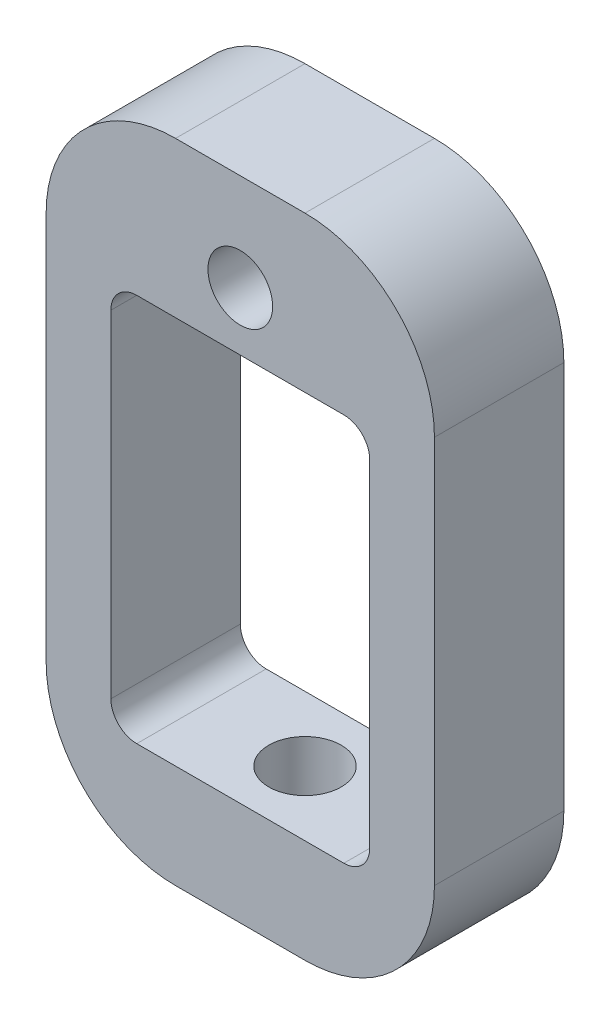
SolidWorks part; units mm, degrees
ref_plane "Front Plane" through (0, 0, 0) normal (0, 0, 1) x (1, 0, 0)
ref_plane "Top Plane" through (0, 0, 0) normal (0, 1, 0) x (1, 0, 0)
ref_plane "Right Plane" through (0, 0, 0) normal (1, 0, 0) x (0, 0, -1)
sketch "Sketch1" plane through (0, 0, 0) normal (0, 0, 1) x (1, 0, 0)
  line L0 (7.5, -25) -> (7.5, 0) construction
  line L1 (0, 0) -> (15, 0)
  line L2 (0, 0) -> (0, -25)
  line L3 (0, -25) -> (15, -25)
  line L4 (15, 0) -> (15, -25)
  line L5 (2.5, -6) -> (12.5, -6)
  line L6 (2.5, -6) -> (2.5, -21)
  line L7 (2.5, -21) -> (12.5, -21)
  line L8 (12.5, -6) -> (12.5, -21)
  line L9 (0, -12.5) -> (15, -12.5) construction
  line L10 (7.5, 0) -> (7.5, -1.75) construction
  circle A0 centre (7.5, -3.75) radius 1.25
  point P15 (7.5, -6)
  dimension "D5" = 2.5
  dimension "D1" = 15
  dimension "D2" = 25
  dimension "D3" = 10
  dimension "D4" = 15
  dimension "D6" = 3.75
  dimension "D7" = 6
extrude "Boss-Extrude1" add sketch "Sketch1" along normal blind 5 contours L8 L7 L6 L5
sketch "Sketch2" plane through (0, -25, 0) normal (0, -1, 0) x (1, 0, 0)
  line L0 (7.5, 0) -> (7.5, 5) construction
  line L1 (0, 0) -> (15, 0) construction
  line L2 (0, 5) -> (15, 5) construction
  line L3 (0, 2.5) -> (7.5, 2.5) construction
  line L4 (0, 5) -> (0, 0) construction
  circle A0 centre (7.5, 2.5) radius 1.4
  dimension "D1" = 2.8
extrude "Cut-Extrude1" cut sketch "Sketch2" against normal up to surface (4 mm away) up to face at (7.5, -21, 2.5)
fillet "Fillet1" radius 5 4 edges at (15, -25, 2.5) (0, -25, 2.5) (15, 0, 2.5) (0, 0, 2.5)
fillet "Fillet2" radius 1 4 edges at (2.5, -6, 2.5) (12.5, -6, 2.5) (12.5, -21, 2.5) (2.5, -21, 2.5)
